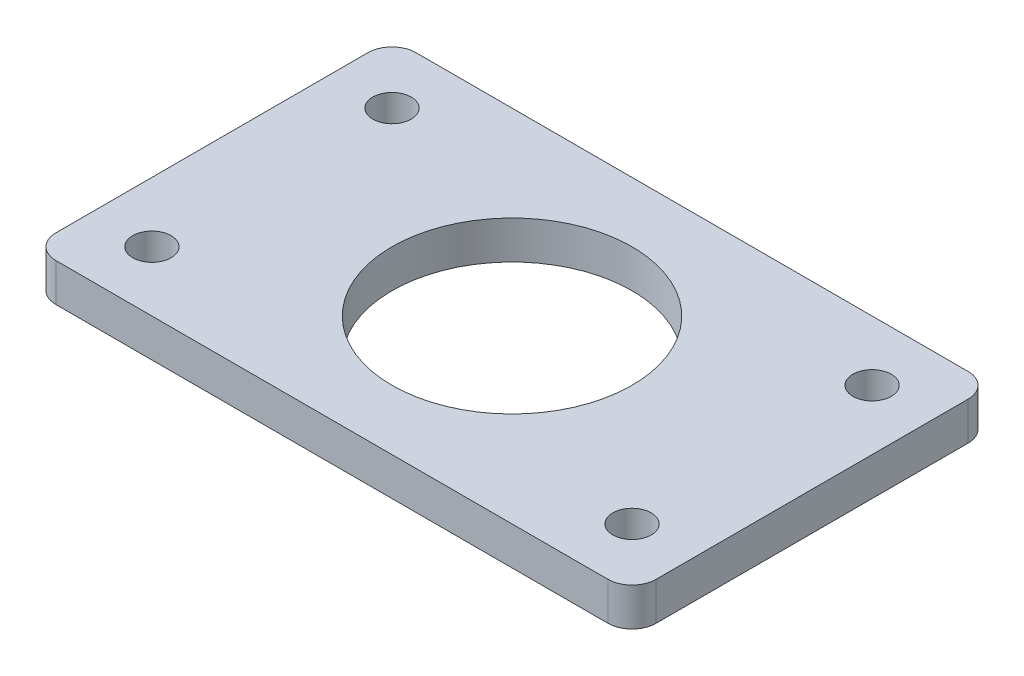
SolidWorks part; units mm, degrees
material "AISI 1045 Steel, cold drawn"
ref_plane "Front Plane" through (0, 0, 0) normal (0, 0, 1) x (1, 0, 0)
ref_plane "Top Plane" through (0, 0, 0) normal (0, 1, 0) x (1, 0, 0)
ref_plane "Right Plane" through (0, 0, 0) normal (1, 0, 0) x (0, 0, -1)
sketch "Sketch1" plane through (0, 0, 0) normal (0, 1, 0) x (1, 0, 0)
  line L1 (25, -15) -> (-25, -15)
  line L2 (25, -15) -> (25, 15)
  line L3 (25, 15) -> (-25, 15)
  line L4 (-25, -15) -> (-25, 15)
  line L5 (25, -15) -> (-25, 15) construction
  line L6 (25, 15) -> (-25, -15) construction
  circle A0 centre (0, 0) radius 10
  dimension "D1" = 20
  dimension "D2" = 30
  dimension "D3" = 50
extrude "Boss-Extrude1" add sketch "Sketch1" along normal blind 3.175
hole_wizard "M3 Clearance Hole1" positions "Sketch4" profile "Sketch3" hole size "M3" standard "ANSI Metric" end condition up to next
sketch "Sketch4" plane through (0, 3.175, 0) normal (0, 1, 0) x (1, 0, 0)
  line L1 (20, -10) -> (-20, -10)
  line L2 (20, -10) -> (20, 10)
  line L3 (20, 10) -> (-20, 10)
  line L4 (-20, -10) -> (-20, 10)
  line L5 (20, -10) -> (-20, 10) construction
  line L6 (20, 10) -> (-20, -10) construction
  line L7 (25, -15) -> (25, 15) construction
  line L8 (25, 15) -> (-25, 15) construction
  point P1 (0, 0)
  point P2 (-20, 10)
  point P119 (20, -10)
  point P120 (20, 10)
  point P121 (-20, -10)
  dimension "D1" = 5
  dimension "D2" = 5
sketch "Sketch3" plane through (0, 3.175, 0) normal (1, 0, 0) x (0, 0, 1)
  line L0 (0, 0) -> (0, 3.175)
  line L1 (0, 3.175) -> (1.6, 3.175)
  line L2 (1.6, 3.175) -> (1.6, 0)
  line L5 (1.6, 0) -> (0, 0)
  line L11 (0, -6.35) -> (0, 107.95) construction
  dimension "Thru Hole Dia." = 3.2
  dimension "Thru Hole Depth" = 3.175
fillet "Fillet1" radius 2 4 edges at (-25, 1.5875, -15) (25, 1.5875, -15) (25, 1.5875, 15) (-25, 1.5875, 15)
